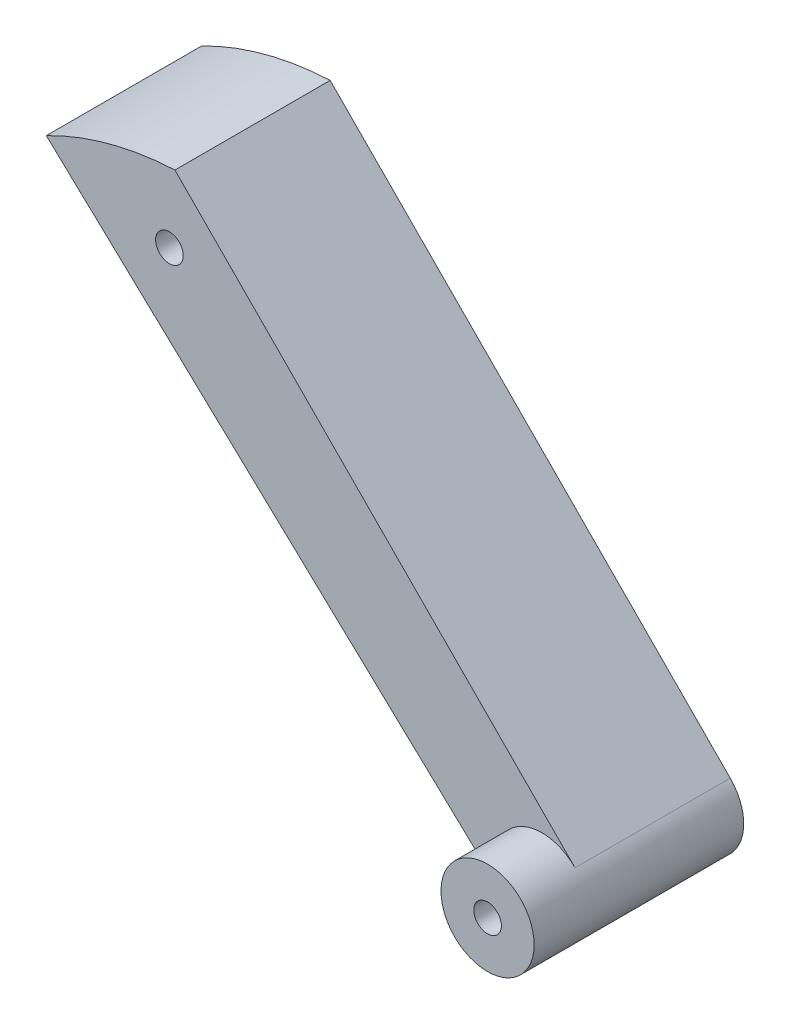
SolidWorks part; units mm, degrees
ref_plane "Front Plane" through (0, 0, 0) normal (0, 0, 1) x (1, 0, 0)
ref_plane "Top Plane" through (0, 0, 0) normal (0, 1, 0) x (1, 0, 0)
ref_plane "Right Plane" through (0, 0, 0) normal (1, 0, 0) x (0, 0, -1)
sketch "Sketch1" plane through (0, 0, 0) normal (0, 0, 1) x (1, 0, 0)
  line L0 (327.0859, -12.8653) -> (291.6497, 22.0439) construction
  line L1 (286.5422, 20.0612) -> (324.4746, -15.6397)
  line L2 (297.0635, 22.8852) -> (329.7938, -10.1852)
  circle A0 centre (296.6131, 17.1543) radius 1.1303
  arc A1 (297.0635, 22.8852) -> (286.5422, 20.0612) centre (298.2342, -2.4878) ccw
  circle A2 centre (327.0859, -12.8653) radius 3.81 construction
  circle A3 centre (327.0859, -12.8653) radius 1.1303
  arc A4 (329.7938, -10.1852) -> (324.4746, -15.6397) centre (327.0859, -12.8653) cw
extrude "Extrude1" add sketch "Sketch1" along normal blind 12.7
sketch "Sketch2" plane through (0, 0, 0) normal (0, 0, 1) x (1, 0, 0)
  circle A0 centre (327.0859, -12.8653) radius 3.81
  circle A1 centre (327.0859, -12.8653) radius 1.1303
extrude "Extrude2" add sketch "Sketch2" along normal blind 17.145
